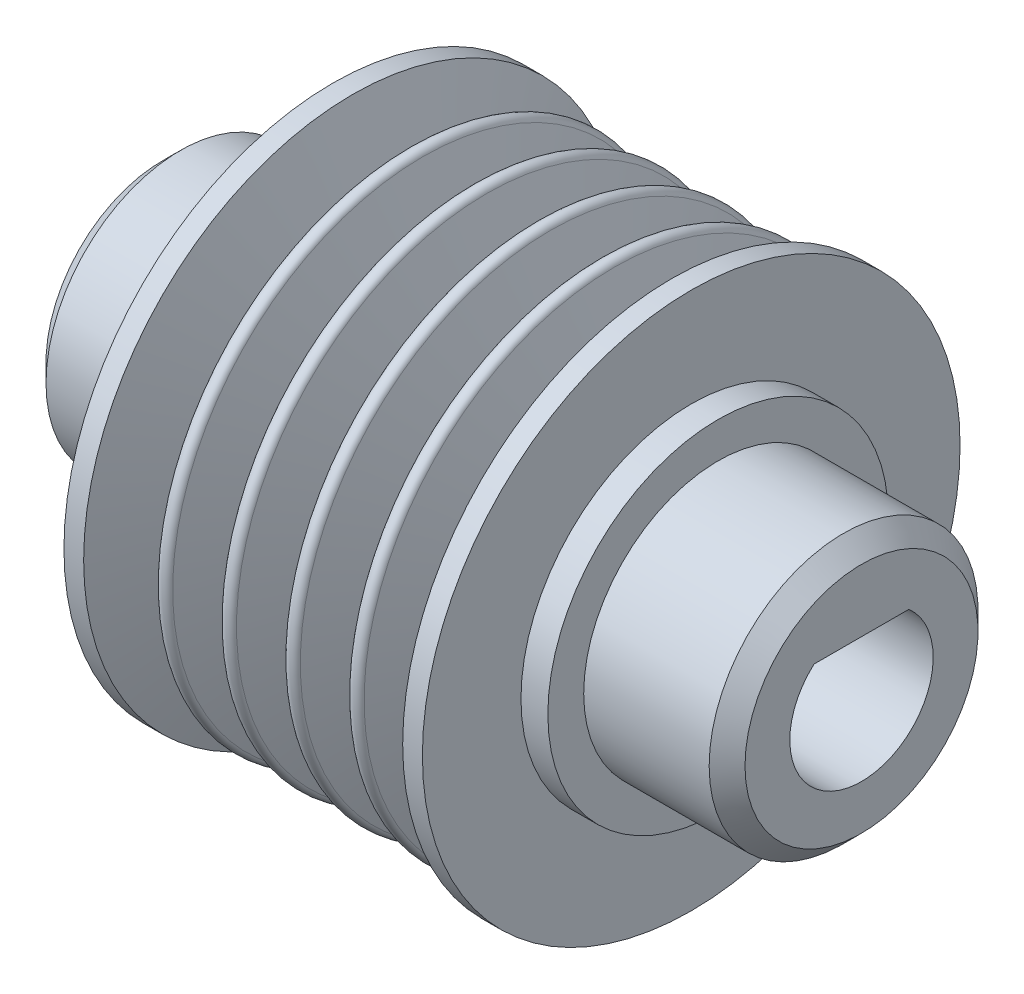
SolidWorks part; units mm, degrees
material "1.0503 (C45)"
ref_plane "Спереди" through (0, 0, 0) normal (0, 0, 1) x (1, 0, 0)
ref_plane "Сверху" through (0, 0, 0) normal (0, 1, 0) x (1, 0, 0)
ref_plane "Справа" through (0, 0, 0) normal (1, 0, 0) x (0, 0, -1)
sketch "Эскиз1" plane through (0, 0, 0) normal (0, 0, 1) x (1, 0, 0)
  line L0 (-17.2156, 0) -> (31.3305, 0) construction
  line L1 (-10, 0) -> (-10, 15) construction
  line L2 (-10, 15) -> (10, 15)
  line L26 (-10, 15) -> (-10, 0)
  line L32 (10, 15) -> (10, 0)
  line L33 (10, 0) -> (-10, 0)
  line L34 (0, 0) -> (0, 50000) construction
  dimension "D1" = 20
  dimension "D2" = 30
revolve "Повернуть1" add sketch "Эскиз1" angle 360 about L0
sketch "Эскиз3" plane through (0, 0, 0) normal (0, 0, 1) x (1, 0, 0)
  line L0 (-11.5, 7.5) -> (-19.5, 7.5)
  line L2 (0, 0) -> (50000, 0) construction
  line L3 (-19.5, 7.5) -> (-19.5, 0)
  line L5 (-10, 0) -> (-19.5, 0)
  line L6 (11.5, 7.5) -> (19.5, 7.5)
  line L8 (19.5, 7.5) -> (19.5, 0)
  line L9 (19.5, 0) -> (10, 0)
  line L11 (-10, 15) -> (-10, -15) construction
  line L12 (-11.5, 7.5) -> (-11.5, 9.5)
  line L13 (-11.5, 9.5) -> (-10, 9.5)
  line L15 (-10, 0) -> (-10, 9.5)
  line L16 (11.5, 7.5) -> (11.5, 9.5)
  line L17 (11.5, 9.5) -> (10, 9.5)
  line L18 (10, 9.5) -> (10, 0)
  line L19 (0, 0) -> (0, 50000) construction
  line L20 (10, -15) -> (10, 15) construction
  dimension "D1" = 15
  dimension "D2" = 1.5
  dimension "D3" = 2
  dimension "D4" = 39
revolve "Повернуть2" add sketch "Эскиз3" angle 360 about L2
sketch "Эскиз8" plane through (0, 0, 0) normal (0, 0, 1) x (1, 0, 0)
  line L0 (-5.34, 15) -> (-7.12, 10.1095)
  line L2 (-7.12, 10.1095) -> (-8.9, 15)
  line L3 (-8.9, 15) -> (-5.34, 15)
  line L4 (-7.12, 11.8204) -> (-7.12, 9.4563) construction
  line L5 (0, 4.7637) -> (0, -1.0769) construction
  line L10 (7.12, 14.8256) -> (7.12, 8.6284) construction
  line L11 (10, 15) -> (-10, 15) construction
  line L12 (-1.78, 15) -> (-3.56, 10.1095)
  line L14 (-3.56, 10.1095) -> (-5.34, 15)
  line L15 (-5.34, 15) -> (-1.78, 15)
  line L16 (1.78, 15) -> (0, 10.1095)
  line L18 (0, 10.1095) -> (-1.78, 15)
  line L19 (-1.78, 15) -> (1.78, 15)
  line L20 (5.34, 15) -> (3.56, 10.1095)
  line L22 (3.56, 10.1095) -> (1.78, 15)
  line L23 (1.78, 15) -> (5.34, 15)
  line L24 (8.9, 15) -> (7.12, 10.1095)
  line L26 (7.12, 10.1095) -> (5.34, 15)
  line L27 (5.34, 15) -> (8.9, 15)
  line L28 (0, 0) -> (-19.2768, 0) construction
  line L29 (-7.12, 14.0333) -> (7.12, 14.0333) construction
  circle A0 centre (-7.12, 13.0333) radius 1 construction
  circle A1 centre (-3.56, 13.0333) radius 1 construction
  circle A2 centre (0, 13.0333) radius 1 construction
  circle A3 centre (3.56, 13.0333) radius 1 construction
  circle A4 centre (7.12, 13.0333) radius 1 construction
  dimension "D3" = 2
  dimension "D1" = 14.24
  dimension "D2" = 40
  dimension "D4" = 5
revolve "Вырез-Повернуть2" cut sketch "Эскиз8" angle 360 about L28
sketch "Эскиз5" plane through (0, 0, 0) normal (1, 0, 0) x (0, 0, -1)
  circle A0 centre (0, 0) radius 4
  dimension "D1" = 8
extrude "Вырез-Вытянуть1" cut sketch "Эскиз5" against normal through all both and the other way through all
sketch "Эскиз6" plane through (0, 0, 0) normal (1, 0, 0) x (0, 0, -1)
  line L0 (0, 0) -> (-50000, 0) construction
  line L1 (0, 0) -> (0, 50000) construction
  line L3 (-1.5, 3.7081) -> (1.5, 3.7081)
  line L4 (-1.5, 3.7081) -> (-1.5, 5)
  line L5 (-1.5, 5) -> (1.5, 5)
  line L6 (1.5, 3.7081) -> (1.5, 5)
  circle A0 centre (0, 0) radius 4 construction
  dimension "D1" = 5
  dimension "D2" = 3
extrude "Вырез-Вытянуть2" [suppressed] cut sketch "Эскиз6" against normal through all both and the other way through all
sketch "Эскиз7" plane through (-19.5, 0, 0) normal (-1, 0, 0) x (0, 0, 1)
  line L0 (-2.6458, 3) -> (2.6458, 3)
  line L1 (0, 0) -> (0, 0.7124) construction
  circle A0 centre (0, 0) radius 4 construction
  arc A2 (2.6458, 3) -> (-2.6458, 3) centre (0, 0) ccw
  dimension "D1" = 3
extrude "Бобышка-Вытянуть1" add sketch "Эскиз7" against normal up to surface (39 mm away) up to face at (19.5, 0, -4)
fillet "Скругление1" radius 0.4 4 edges at (5.34, 15, 0) (1.78, 15, 0) (-1.78, 15, 0) (-5.34, 15, 0)
chamfer "Фаска1" distance 1 angle 45 2 edges at (19.5, 0, 7.5) (-19.5, 0, 7.5)
fillet "Скругление2" radius 0.4 5 edges at (7.12, 10.1095, 0) (3.56, 10.1095, 0) (0, 10.1095, 0) (-3.56, 10.1095, 0) (-7.12, 10.1095, 0)
